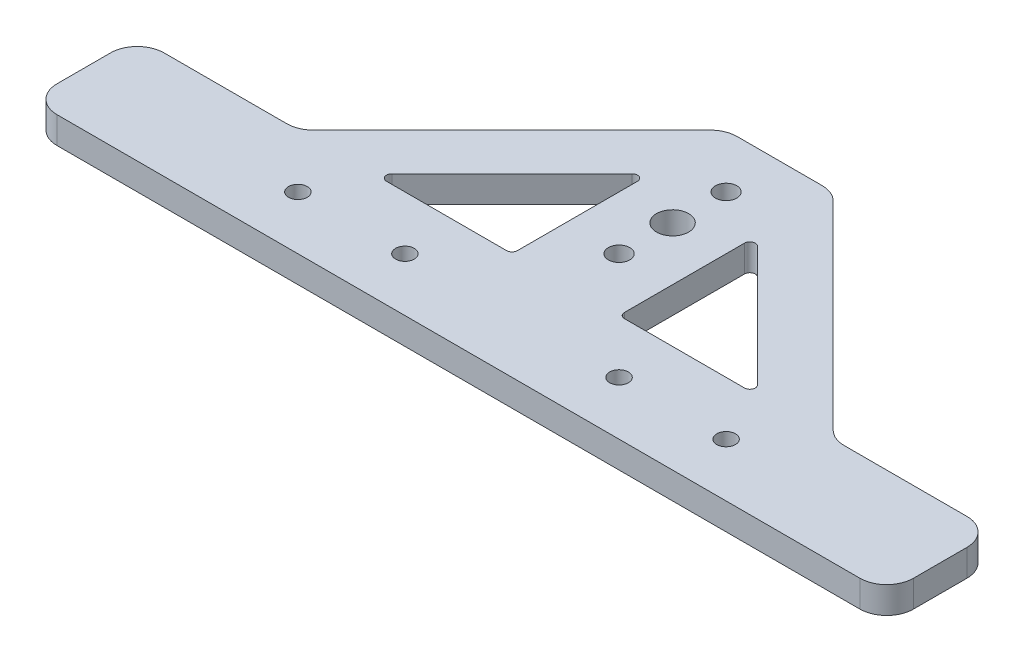
SolidWorks part; units mm, degrees
ref_plane "Plano frontal" through (0, 0, 0) normal (0, 0, 1) x (1, 0, 0)
ref_plane "Plano superior" through (0, 0, 0) normal (0, 1, 0) x (1, 0, 0)
ref_plane "Plano direito" through (0, 0, 0) normal (1, 0, 0) x (0, 0, -1)
sketch "Esboço1" plane through (0, 0, 0) normal (0, 1, 0) x (1, 0, 0)
  line L0 (-50, 0) -> (-50, 20)
  line L1 (-10, 60) -> (10, 60)
  line L2 (10, 60) -> (50, 20)
  line L3 (50, 20) -> (50, 0)
  line L4 (50, 0) -> (-50, 0)
  line L5 (-10, 43.4437) -> (-10, 21)
  line L6 (-33.4437, 20) -> (-11, 20)
  line L7 (-11.7071, 44.1508) -> (-34.1508, 21.7071)
  line L8 (0, 60) -> (0, 0) construction
  line L9 (-50, 10) -> (50, 10) construction
  line L10 (-10, 60) -> (-50, 20)
  line L11 (11.7071, 44.1508) -> (34.1508, 21.7071)
  line L12 (33.4437, 20) -> (11, 20)
  line L13 (10, 43.4437) -> (10, 21)
  arc A0 (-10, 21) -> (-11, 20) centre (-11, 21) cw
  arc A1 (-33.4437, 20) -> (-34.1508, 21.7071) centre (-33.4437, 21) cw
  arc A2 (-11.7071, 44.1508) -> (-10, 43.4437) centre (-11, 43.4437) cw
  circle A3 centre (-40, 10) radius 1.75
  circle A4 centre (-20, 10) radius 1.75
  circle A5 centre (0, 50) radius 1.75
  circle A6 centre (0, 30) radius 1.75
  circle A7 centre (20, 10) radius 1.75
  circle A8 centre (40, 10) radius 1.75
  arc A9 (11.7071, 44.1508) -> (10, 43.4437) centre (11, 43.4437) ccw
  arc A10 (33.4437, 20) -> (34.1508, 21.7071) centre (33.4437, 21) ccw
  arc A11 (10, 21) -> (11, 20) centre (11, 21) ccw
  dimension "D1" = 1
  dimension "D2" = 3.5
  dimension "D3" = 10
  dimension "D4" = 20
  dimension "D5" = 10
  dimension "D6" = 10
  dimension "D7" = 10
  dimension "D8" = 10
  dimension "D9" = 45
  dimension "D10" = 60
  dimension "D11" = 20
  dimension "D12" = 100
  dimension "D13" = 20
extrude "Ressalto-extrusão1" add sketch "Esboço1" along normal blind 5
sketch "Esboço3" plane through (0, 5, 0) normal (0, 1, 0) x (1, 0, 0)
  line L0 (-40, 10) -> (-20, 10) construction
  line L1 (-50, 20) -> (-50, 0) construction
  line L2 (-10, 7.175) -> (-50, 7.175)
  line L3 (-10, 7.175) -> (-10, 12.825)
  line L4 (-10, 12.825) -> (-50, 12.825)
  line L5 (-50, 7.175) -> (-50, 12.825)
  line L6 (-10, 7.175) -> (-50, 12.825) construction
  line L7 (-10, 12.825) -> (-50, 7.175) construction
  line L8 (20, 10) -> (40, 10) construction
  line L9 (50, 0) -> (50, 20) construction
  line L10 (10, 12.825) -> (50, 12.825)
  line L11 (10, 12.825) -> (10, 7.175)
  line L12 (10, 7.175) -> (50, 7.175)
  line L13 (50, 12.825) -> (50, 7.175)
  line L14 (10, 12.825) -> (50, 7.175) construction
  line L15 (10, 7.175) -> (50, 12.825) construction
  point P4 (-30, 10)
  point P17 (30, 10)
  circle M10 centre (40, 10) radius 1.75
  circle M11 centre (20, 10) radius 1.75
  circle M13 centre (-20, 10) radius 1.75
  circle M14 centre (-40, 10) radius 1.75
  line M22 (50, 0) -> (50, 20)
  line M26 (-50, 20) -> (-50, 0)
  dimension "D1" = 5.65
extrude "Ressalto-extrusão2" [suppressed] add sketch "Esboço3" along normal blind 1 contours L3 L4 L2 M26 M13 M14 | L11 L12 L10 M22 M11 M10
sketch "Esboço4" plane through (0, 0, 0) normal (0, -1, 0) x (1, 0, 0)
  line L0 (-50, -20) -> (-80, -20)
  line L1 (-80, -20) -> (-80, 0)
  line L2 (-80, 0) -> (-50, 0)
  line L3 (-50, 0) -> (-50, -20)
  line L4 (50, 0) -> (80, 0)
  line L5 (80, 0) -> (80, -20)
  line L6 (80, -20) -> (50, -20)
  line L7 (50, 0) -> (50, -20)
  line M10 (-50, 0) -> (-50, -20)
  line M14 (50, -20) -> (50, 0)
  dimension "D1" = 30
extrude "Ressalto-extrusão3" add sketch "Esboço4" against normal up to surface (5 mm away) contours L2 L1 L0 M10 | L6 L5 L4 M14 up to face at (0, 5, -28.25)
sketch "Esboço5" plane through (0, 0, 0) normal (0, -1, 0) x (1, 0, 0)
  line L0 (0, -30) -> (0, -50) construction
  circle A0 centre (0, -40) radius 3
  dimension "D1" = 6
extrude "Corte-extrusão1" cut sketch "Esboço5" against normal through all
sketch "Esboço6" plane through (0, 0, 0) normal (0, -1, 0) x (1, 0, 0)
  circle A0 centre (0, -30) radius 1.75 construction
  circle A1 centre (0, -30) radius 1.75
  circle A2 centre (0, -50) radius 1.75 construction
  circle A3 centre (0, -50) radius 1.75
extrude "Ressalto-extrusão5" add sketch "Esboço6" against normal through all
fillet "Filete1" radius 5 8 edges at (-80, 2.5, 0) (-80, 2.5, -20) (-50, 2.5, -20) (-10, 2.5, -60) (10, 2.5, -60) (50, 2.5, -20) (80, 2.5, 0) (80, 2.5, -20)
sketch "Esboço7" plane through (0, 0, 0) normal (0, -1, 0) x (1, 0, 0)
  line L0 (0, -40) -> (0, -50) construction
  line L1 (0, -40) -> (0, -30) construction
  circle A0 centre (0, -50) radius 2
  circle A1 centre (0, -30) radius 2
  dimension "D2" = 4
  dimension "D1" = 10
extrude "Corte-extrusão2" cut sketch "Esboço7" against normal through all
